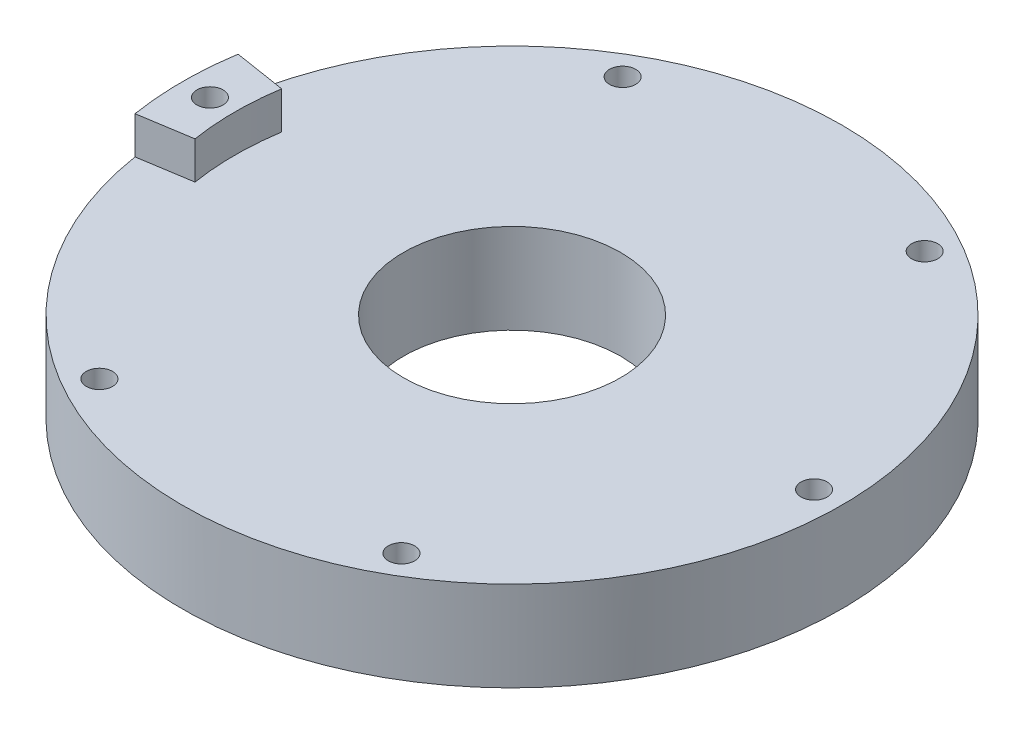
SolidWorks part; units mm, degrees
ref_plane "Ön Düzlem" through (0, 0, 0) normal (0, 0, 1) x (1, 0, 0)
ref_plane "Üst Düzlem" through (0, 0, 0) normal (0, 1, 0) x (1, 0, 0)
ref_plane "Sağ Düzlem" through (0, 0, 0) normal (1, 0, 0) x (0, 0, -1)
sketch "Sketch1" plane through (0, 0, 0) normal (0, 0, 1) x (1, 0, 0)
  line L0 (0, 0) -> (0, 12) construction
  line L1 (14.5, 0) -> (44, 0)
  line L2 (14.5, 0) -> (14.5, 12)
  line L3 (14.5, 12) -> (44, 12)
  line L4 (44, 0) -> (44, 12)
  line L5 (14.5, 0) -> (44, 12) construction
  line L6 (14.5, 12) -> (44, 0) construction
  point P0 (29.25, 6)
  dimension "D1" = 44
  dimension "D2" = 12
  dimension "D3" = 14.5
revolve "Revolve1" add sketch "Sketch1" angle 360 about L0
sketch "Sketch2" plane through (0, 12, 0) normal (0, 1, 0) x (1, 0, 0)
  line L0 (0, 0) -> (-44, 0) construction
  line L1 (0, 0) -> (-43.4583, 6.8831)
  line L2 (0, 0) -> (-43.4583, -6.8831)
  circle A0 centre (0, 0) radius 44 construction
  circle A1 centre (0, 0) radius 44
  circle A2 centre (0, 0) radius 37
  circle M2 centre (0, 0) radius 44
  dimension "D2" = 9
  dimension "D1" = 7
extrude "Boss-Extrude1" add sketch "Sketch2" along normal blind 5 contours L0 A2 L1 M2 | A2 L0 A1 L2
sketch "Sketch3" plane through (0, 17, 0) normal (0, 1, 0) x (1, 0, 0)
  circle A0 centre (-40.3329, 0) radius 1.75
  dimension "D1" = 3.5
extrude "Cut-Extrude1" cut sketch "Sketch3" against normal through all
pattern_circular "CirPattern1" count 6 over 360 about axis through (0, 0, 0) along (0, 1, 0) of "Cut-Extrude1"
